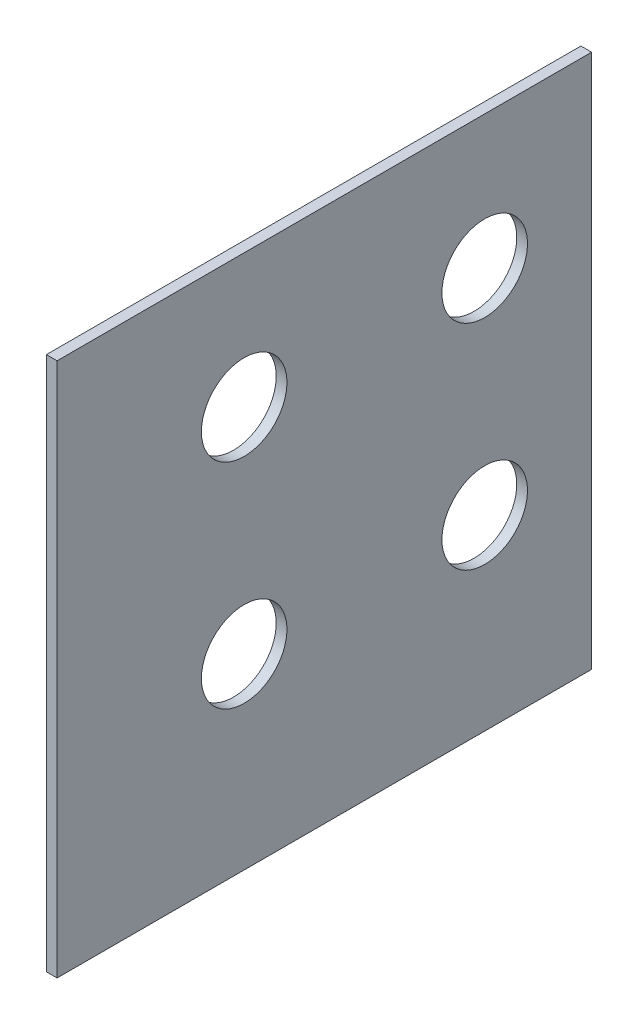
SolidWorks part; units mm, degrees
ref_plane "Front Plane" through (0, 0, 0) normal (0, 0, 1) x (1, 0, 0)
ref_plane "Top Plane" through (0, 0, 0) normal (0, 1, 0) x (1, 0, 0)
ref_plane "Right Plane" through (0, 0, 0) normal (1, 0, 0) x (0, 0, -1)
sketch "Sketch1" plane through (0, 0, 0) normal (1, 0, 0) x (0, 0, -1)
  line L1 (-122.3069, -23.3926) -> (-142.3069, -23.3926)
  line L2 (-122.3069, -23.3926) -> (-122.3069, -3.3926)
  line L3 (-122.3069, -3.3926) -> (-142.3069, -3.3926)
  line L4 (-142.3069, -23.3926) -> (-142.3069, -3.3926)
  dimension "D1" = 20
  dimension "D2" = 20
extrude "Boss-Extrude1" add sketch "Sketch1" along normal blind 0.4
sketch "Sketch2" plane through (0, 0, 0) normal (-1, 0, 0) x (0, 0, 1)
  line L0 (122.3069, -3.3926) -> (142.3069, -3.3926) construction
  line L1 (122.3069, -23.3926) -> (122.3069, -3.3926) construction
  line L2 (142.3069, -3.3926) -> (142.3069, -23.3926) construction
  circle A0 centre (126.3069, -8.3926) radius 1.6
  circle A1 centre (126.3069, -16.3926) radius 1.6
  circle A2 centre (135.3069, -8.3926) radius 1.6
  circle A3 centre (135.3069, -16.3926) radius 1.6
  dimension "D1" = 3.2
  dimension "D2" = 3.2
  dimension "D3" = 3.2
  dimension "D4" = 3.2
  dimension "D5" = 5
  dimension "D6" = 4
  dimension "D7" = 4
  dimension "D8" = 13
  dimension "D9" = 5
  dimension "D10" = 13
  dimension "D11" = 7
  dimension "D12" = 7
extrude "Cut-Extrude1" cut sketch "Sketch2" against normal blind 0.4
